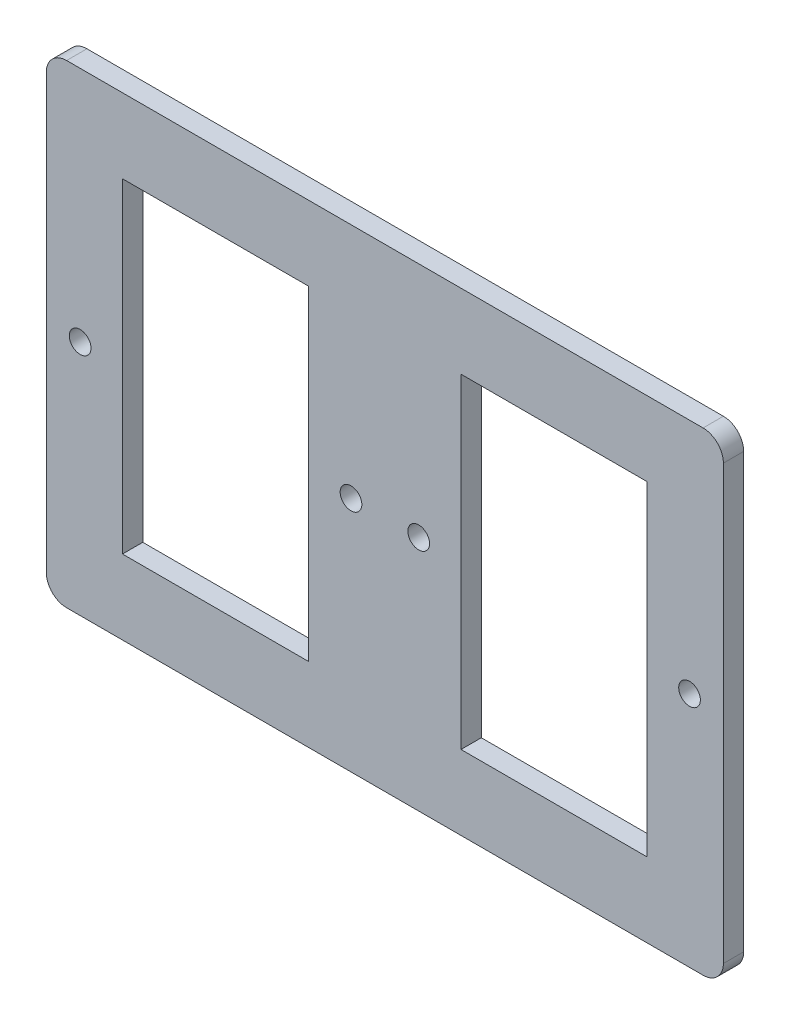
SolidWorks part; units mm, degrees
material "6061-T6 (SS)"
ref_plane "Front Plane" through (0, 0, 0) normal (0, 0, 1) x (1, 0, 0)
ref_plane "Top Plane" through (0, 0, 0) normal (0, 1, 0) x (1, 0, 0)
ref_plane "Right Plane" through (0, 0, 0) normal (1, 0, 0) x (0, 0, -1)
sketch "Sketch1" plane through (0, 0, 0) normal (0, 0, 1) x (1, 0, 0)
  line L0 (-25, 0) -> (0, 0) construction
  line L1 (-11.25, -24) -> (-38.75, -24)
  line L2 (-11.25, -24) -> (-11.25, 24)
  line L3 (-11.25, 24) -> (-38.75, 24)
  line L4 (-38.75, -24) -> (-38.75, 24)
  line L5 (-11.25, -24) -> (-38.75, 24) construction
  line L6 (-11.25, 24) -> (-38.75, -24) construction
  line L11 (11.25, 24) -> (38.75, 24)
  line L12 (50, -35) -> (-50, -35)
  line L13 (-5, 0) -> (-45, 0) construction
  line L14 (0, -1000) -> (0, 49000) construction
  line L15 (50, -35) -> (50, 35)
  line L16 (50, 35) -> (-50, 35)
  line L17 (-50, -35) -> (-50, 35)
  line L18 (50, -35) -> (-50, 35) construction
  line L19 (50, 35) -> (-50, -35) construction
  line L20 (38.75, -24) -> (38.75, 24)
  line L21 (11.25, -24) -> (38.75, -24)
  line L22 (11.25, -24) -> (11.25, 24)
  point P0 (-25, 0)
  point P18 (-25, 0)
  dimension "D1" = 27.5
  dimension "D2" = 48
  dimension "D3" = 40
  dimension "D4" = 25
  dimension "D5" = 70
  dimension "D6" = 100
extrude "Boss-Extrude1" add sketch "Sketch1" along normal blind 3
hole_wizard "M3 Clearance Hole1" positions "Sketch2" profile "Sketch3" hole size "M3" standard "ANSI Metric" end condition up to next
sketch "Sketch2" plane through (0, 0, 3) normal (0, 0, 1) x (1, 0, 0)
  line L1 (0, -1.65) -> (0, 1.65) construction
  point P0 (-45, 0)
  point P3 (-5, 0)
  point P9 (0, 0)
  point P12 (45, 0)
  point P13 (5, 0)
sketch "Sketch3" plane through (-45, 0, 3) normal (1, 0, 0) x (0, -1, 0)
  line L0 (0, 0) -> (0, 3)
  line L1 (0, 3) -> (1.6, 3)
  line L2 (1.6, 3) -> (1.6, 0)
  line L5 (1.6, 0) -> (0, 0)
  line L11 (0, -6.35) -> (0, 107.95) construction
  dimension "Thru Hole Dia." = 3.2
  dimension "Thru Hole Depth" = 3
fillet "Fillet1" radius 3 4 edges at (50, 35, 1.5) (50, -35, 1.5) (-50, -35, 1.5) (-50, 35, 1.5)
